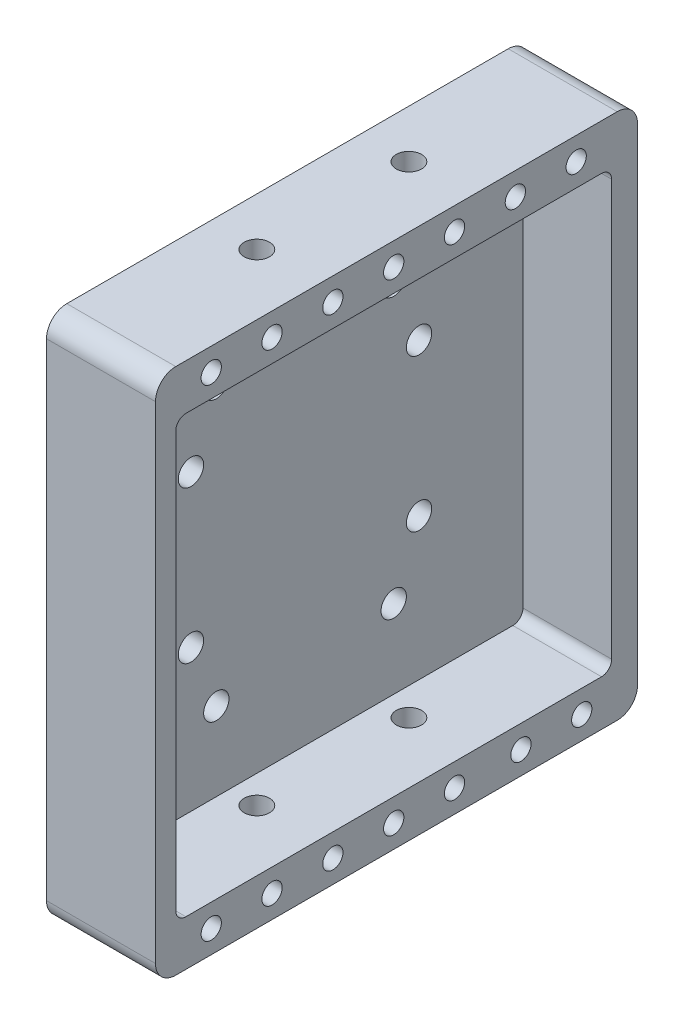
SolidWorks part; units mm, degrees
ref_plane "前视基准面" through (0, 0, 0) normal (0, 0, 1) x (1, 0, 0)
ref_plane "上视基准面" through (0, 0, 0) normal (0, 1, 0) x (1, 0, 0)
ref_plane "右视基准面" through (0, 0, 0) normal (1, 0, 0) x (0, 0, -1)
other "Configuration Table"
ref_plane "基准面1" through (0, 0, 0) normal (-1, 0, 0) x (0, -1, 0)
sketch "草图1" plane through (0, 0, 0) normal (-1, 0, 0) x (0, -1, 0)
  line L0 (-52, 47) -> (-52, -48.0964)
  line L1 (-52, -48.0964) -> (52, -48.0964)
  line L2 (52, -48.0964) -> (52, 47)
  line L3 (52, 47) -> (-52, 47)
extrude "凸台-拉伸1" add sketch "草图1" against normal blind 21.5
sketch "草图2" plane through (21.5, 0, 0) normal (1, 0, 0) x (0, 0, -1)
  line L0 (43, -43) -> (43, 43)
  line L1 (43, 43) -> (-43, 43)
  line L2 (-43, 43) -> (-43, -43)
  line L3 (-43, -43) -> (43, -43)
extrude "切除-拉伸1" cut sketch "草图2" against normal blind 17.5
hole_wizard "Ø4.0 (4) 直径孔1" positions "草图4" profile "草图3" hole size "Ø4.0" standard "ANSI Metric"
sketch "草图4" plane through (21.5, 0, 0) normal (1, 0, 0) x (0, 0, -1)
  line L0 (48.0964, 52) -> (48.0964, -52) construction
  point P0 (0, 47.5)
  point P1 (12, 47.5)
  point P2 (24, 47.5)
  point P3 (-12, 47.5)
  point P4 (-24, 47.5)
  point P5 (0, -47.5)
  point P6 (12, -47.5)
  point P7 (25.0964, -47.5)
  point P8 (-12, -47.5)
  point P9 (-24, -47.5)
  point P10 (36, 47.5)
  point P11 (37.0964, -47.5)
  point P12 (-36, -47.5)
  point P13 (-36, 47.5)
  dimension "D1" = 11
  dimension "D2" = 12
sketch "草图3" plane through (21.5, 47.5, 0) normal (0, 1, 0) x (0, 0, -1)
  line L0 (0, 0) -> (0, 8)
  line L1 (0, 8) -> (2, 8)
  line L2 (2, 8) -> (2, 0)
  line L5 (2, 0) -> (0, 0)
  line L10 (0, 8) -> (-2, 8) construction
  line L11 (0, -6.35) -> (0, 107.95) construction
  dimension "孔直径" = 4
  dimension "孔深度" = 8
  dimension "导头角度" = 180
hole_wizard "Ø5.0 (5) 直径孔1" positions "草图6" profile "草图5" hole size "Ø5.0" standard "ANSI Metric"
sketch "草图6" plane through (0, -52, 0) normal (0, -1, 0) x (-1, 0, 0)
  point P0 (-9.5, 15)
  point P1 (-9.5, -15)
sketch "草图5" plane through (9.5, -52, -15) normal (1, 0, 0) x (0, 0, -1)
  line L0 (0, 0) -> (0, 9)
  line L1 (0, 9) -> (2.5, 9)
  line L2 (2.5, 9) -> (2.5, 0)
  line L5 (2.5, 0) -> (0, 0)
  line L11 (0, -6.35) -> (0, 107.95) construction
  dimension "通孔孔直径" = 5
  dimension "通孔孔深度" = 9
hole_wizard "Ø5.0 (5) 直径孔2" positions "草图8" profile "草图7" hole size "Ø5.0" standard "ANSI Metric"
sketch "草图8" plane through (0, 0, 0) normal (-1, 0, 0) x (0, 0, 1)
  point P0 (-17.5, -27.5)
  point P1 (-17.5, 27.5)
  point P2 (17.5, 27.5)
  point P3 (17.5, -27.5)
  point P4 (-22.5, -15)
  point P5 (-22.5, 15)
  point P6 (22.5, 15)
  point P7 (22.5, -15)
sketch "草图7" plane through (0, -27.5, -17.5) normal (0, 1, 0) x (0, 0, 1)
  line L0 (0, 0) -> (0, 21.5)
  line L1 (0, 21.5) -> (2.5, 21.5)
  line L2 (2.5, 21.5) -> (2.5, 0)
  line L5 (2.5, 0) -> (0, 0)
  line L11 (0, -6.35) -> (0, 107.95) construction
  dimension "通孔孔直径" = 5
  dimension "通孔孔深度" = 21.5
hole_wizard "Ø5.0 (5) 直径孔3" positions "草图10" profile "草图9" hole size "Ø5.0" standard "ANSI Metric"
sketch "草图10" plane through (0, 52, 0) normal (0, 1, 0) x (1, 0, 0)
  point P0 (9.5, -15)
  point P1 (9.5, 15)
sketch "草图9" plane through (9.5, 52, 15) normal (1, 0, 0) x (0, 0, 1)
  line L0 (0, 0) -> (0, 104)
  line L1 (0, 104) -> (2.5, 104)
  line L2 (2.5, 104) -> (2.5, 0)
  line L5 (2.5, 0) -> (0, 0)
  line L11 (0, -6.35) -> (0, 107.95) construction
  dimension "通孔孔直径" = 5
  dimension "通孔孔深度" = 104
fillet "圆角1" radius 2 4 edges at (12.75, 43, 43) (12.75, -43, 43) (12.75, -43, -43) (12.75, 43, -43)
fillet "圆角2" radius 4 4 edges at (10.75, 52, -48.0964) (10.75, -52, -48.0964) (10.75, 52, 47) (10.75, -52, 47)
